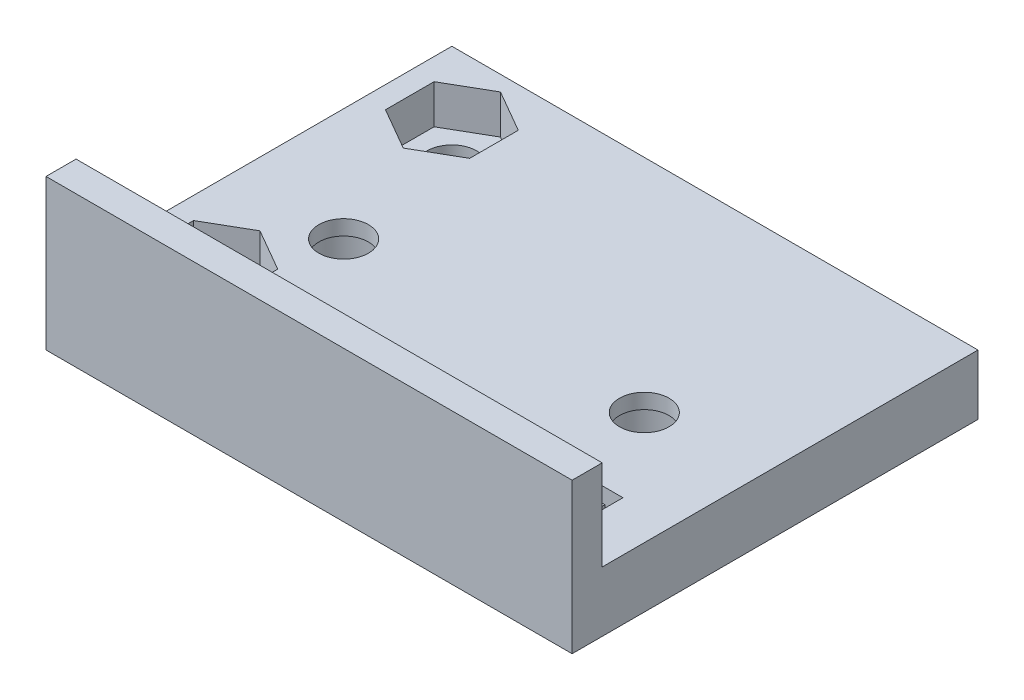
SolidWorks part; units mm, degrees
ref_plane "Front Plane" through (0, 0, 0) normal (0, 0, 1) x (1, 0, 0)
ref_plane "Top Plane" through (0, 0, 0) normal (0, 1, 0) x (1, 0, 0)
ref_plane "Right Plane" through (0, 0, 0) normal (1, 0, 0) x (0, 0, -1)
sketch "Sketch3" plane through (0, 0, 0) normal (0, 1, 0) x (1, 0, 0)
  line L0 (-17.5, -11.5) -> (17.5, -11.5) construction
  line L1 (-17.5, -13.5) -> (17.5, -13.5)
  line L2 (-17.5, -13.5) -> (-17.5, 13.5)
  line L3 (-17.5, 13.5) -> (17.5, 13.5)
  line L4 (17.5, -13.5) -> (17.5, 13.5)
  line L5 (-17.5, -13.5) -> (17.5, 13.5) construction
  line L6 (-17.5, 13.5) -> (17.5, -13.5) construction
  line L7 (0, 13.5) -> (0, -13.5) construction
  circle A0 centre (10, -1.2) radius 1.65
  circle A1 centre (-10, -1.2) radius 1.65
  point P0 (0, 0)
  dimension "D6" = 3.3
  dimension "D1" = 35
  dimension "D2" = 27
  dimension "D3" = 25
  dimension "D4" = 10.3
  dimension "D5" = 7.5
extrude "Boss-Extrude2" add sketch "Sketch3" along normal blind 4
sketch "Sketch5" plane through (0, 4, 0) normal (0, 1, 0) x (1, 0, 0)
  line L0 (-17.5, -11.5) -> (17.5, -11.5)
  line L1 (-17.5, 13.5) -> (-17.5, -13.5) construction
  line L2 (17.5, -13.5) -> (17.5, 13.5) construction
  line L3 (17.5, -11.5) -> (17.5, -13.5)
  line L4 (17.5, -13.5) -> (-17.5, -13.5)
  line L5 (-17.5, -13.5) -> (-17.5, -11.5)
  line L6 (17.5, 13.5) -> (-17.5, 13.5) construction
  dimension "D1" = 25
extrude "Boss-Extrude3" add sketch "Sketch5" along normal blind 6
sketch "Sketch7" plane through (0, 0, 0) normal (0, -1, 0) x (1, 0, 0)
  line L0 (0.25, -1.25) -> (-15.5, -1.25) construction
  line L1 (-15.5, -11.5) -> (0.25, -11.5) construction
  line L2 (-15.5, -11.5) -> (-15.5, 9) construction
  line L3 (-15.5, 9) -> (0.25, 9) construction
  line L4 (0.25, -11.5) -> (0.25, 9) construction
  line L5 (17.5, -13.5) -> (-17.5, -13.5) construction
  line L6 (-17.5, -13.5) -> (-17.5, 13.5) construction
  circle A0 centre (-13.25, -9.25) radius 1.65
  circle A1 centre (-13.25, 6.75) radius 1.65
  dimension "D7" = 3.3
  dimension "D1" = 15.75
  dimension "D2" = 20.5
  dimension "D3" = 2.25
  dimension "D4" = 2.25
  dimension "D5" = 2
  dimension "D6" = 2
extrude "Cut-Extrude2" cut sketch "Sketch7" against normal up to surface (4 mm away) up to face at (-10, 4, -0.45)
sketch "Sketch8" plane through (0, 4, 0) normal (0, 1, 0) x (1, 0, 0)
  line L1 (-10.45, 7.6334) -> (-10.45, 10.8666)
  line L2 (-10.45, 10.8666) -> (-13.25, 12.4832)
  line L3 (-13.25, 12.4832) -> (-16.05, 10.8666)
  line L4 (-16.05, 10.8666) -> (-16.05, 7.6334)
  line L5 (-16.05, 7.6334) -> (-13.25, 6.0168)
  line L6 (-13.25, 6.0168) -> (-10.45, 7.6334)
  line L7 (-10.45, -5.1334) -> (-13.25, -3.5168)
  line L8 (-13.25, -3.5168) -> (-16.05, -5.1334)
  line L9 (-16.05, -5.1334) -> (-16.05, -8.3666)
  line L10 (-16.05, -8.3666) -> (-13.25, -9.9832)
  line L11 (-13.25, -9.9832) -> (-10.45, -8.3666)
  line L12 (-10.45, -8.3666) -> (-10.45, -5.1334)
  circle A0 centre (-13.25, 9.25) radius 2.8 construction
  circle A1 centre (-13.25, -6.75) radius 2.8 construction
  dimension "D1" = 5.6
extrude "Cut-Extrude3" cut sketch "Sketch8" against normal blind 2.6
sketch "Sketch9" plane through (0, 0, 0) normal (0, -1, 0) x (1, 0, 0)
  circle A0 centre (-10, 1.2) radius 2.7
  circle A1 centre (10, 1.2) radius 2.7
  dimension "D1" = 5.4
extrude "Cut-Extrude4" cut sketch "Sketch9" against normal blind 3
sketch "Sketch10" plane through (0, 0, 0) normal (0, -1, 0) x (1, 0, 0)
  line L0 (10, 13.5) -> (10, 1.2) construction
  line L1 (-17.5, 13.5) -> (17.5, 13.5) construction
  line L2 (7, 6.8191) -> (7, 9.6191)
  line L3 (14.2, 6.8191) -> (13, 6.8191)
  line L4 (14.2, 6.8191) -> (14.2, 9.6191)
  line L5 (14.2, 9.6191) -> (13, 9.6191)
  line L6 (13, 6.8191) -> (13, 9.6191)
  line L7 (14.2, 6.8191) -> (13, 9.6191) construction
  line L8 (14.2, 9.6191) -> (13, 6.8191) construction
  line L9 (5.8, 9.6191) -> (7, 9.6191)
  line L10 (5.8, 6.8191) -> (5.8, 9.6191)
  line L11 (5.8, 6.8191) -> (7, 6.8191)
  point P4 (13.6, 8.2191)
  dimension "D1" = 1.2
  dimension "D2" = 2.8
  dimension "D3" = 3.8809
  dimension "D4" = 6
extrude "Cut-Extrude5" cut sketch "Sketch10" against normal up to surface (4 mm away) up to face at (-13.25, 4, -9.25)
sketch "Sketch11" plane through (0, 4, 0) normal (0, 1, 0) x (1, 0, 0)
  line L0 (7, -6.8191) -> (13, -6.8191)
  line L1 (13, -6.8191) -> (13, -9.6191)
  line L2 (13, -9.6191) -> (7, -9.6191)
  line L3 (7, -9.6191) -> (7, -6.8191)
extrude "Cut-Extrude6" cut sketch "Sketch11" against normal blind 1
